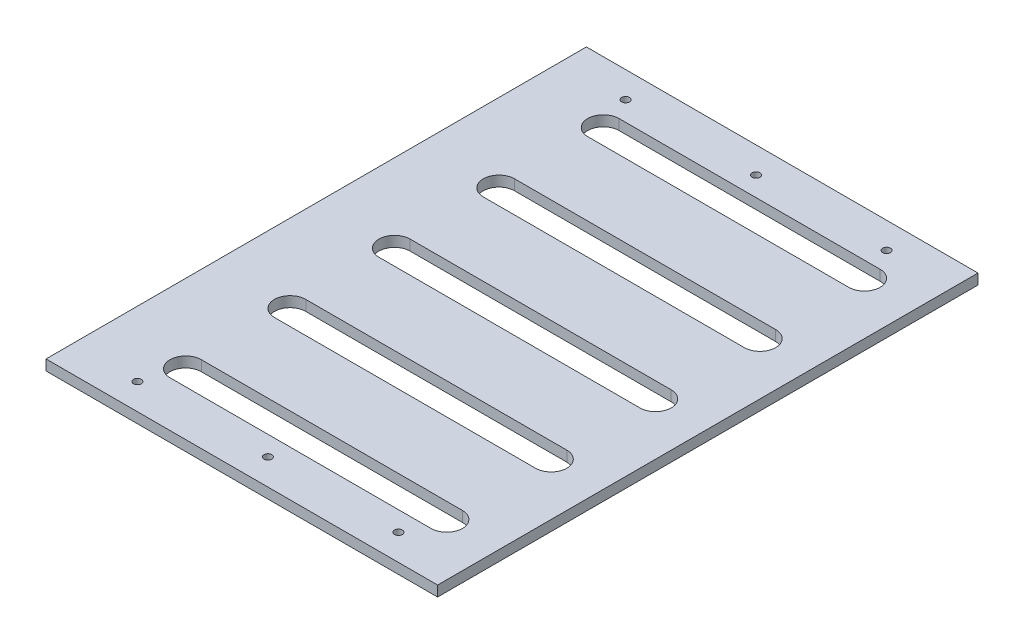
SolidWorks part; units mm, degrees
ref_plane "Front" through (0, 0, 0) normal (0, 0, 1) x (1, 0, 0)
ref_plane "Top" through (0, 0, 0) normal (0, 1, 0) x (1, 0, 0)
ref_plane "Right" through (0, 0, 0) normal (1, 0, 0) x (0, 0, -1)
sketch "草图1" plane through (0, 0, 0) normal (0, 1, 0) x (1, 0, 0)
  line L1 (0, 0) -> (150, 0)
  line L2 (0, 0) -> (0, 207)
  line L3 (0, 207) -> (150, 207)
  line L4 (150, 0) -> (150, 207)
  dimension "D1" = 150
  dimension "D2" = 207
extrude "凸台-拉伸1" add sketch "草图1" along normal blind 4
sketch "草图2" plane through (0, 4, 0) normal (0, 1, 0) x (1, 0, 0)
  line L0 (30, 183.5) -> (130, 183.5) construction
  line L1 (30, 189.5) -> (130, 189.5)
  line L2 (30, 177.5) -> (130, 177.5)
  line L4 (150, 103.5) -> (0, 103.5) construction
  line L5 (150, 0) -> (150, 207) construction
  line L6 (0, 207) -> (0, 0) construction
  line L7 (30, 143.5) -> (130, 143.5) construction
  line L8 (30, 149.5) -> (130, 149.5)
  line L9 (30, 137.5) -> (130, 137.5)
  line L13 (30, 103.5) -> (130, 103.5) construction
  line L14 (30, 97.5) -> (130, 97.5)
  line L15 (30, 109.5) -> (130, 109.5)
  line L16 (30, 63.5) -> (130, 63.5) construction
  line L17 (30, 57.5) -> (130, 57.5)
  line L18 (30, 69.5) -> (130, 69.5)
  line L19 (30, 23.5) -> (130, 23.5) construction
  line L20 (30, 17.5) -> (130, 17.5)
  line L21 (30, 29.5) -> (130, 29.5)
  line L24 (30, 103.5) -> (130, 103.5) construction
  line L25 (30, 109.5) -> (130, 109.5)
  line L26 (30, 97.5) -> (130, 97.5)
  line L27 (30, 103.5) -> (130, 103.5) construction
  line L28 (30, 109.5) -> (130, 109.5)
  line L29 (30, 97.5) -> (130, 97.5)
  arc A0 (30, 189.5) -> (30, 177.5) centre (30, 183.5) ccw
  arc A1 (130, 177.5) -> (130, 189.5) centre (130, 183.5) ccw
  arc A2 (30, 149.5) -> (30, 137.5) centre (30, 143.5) ccw
  arc A3 (130, 137.5) -> (130, 149.5) centre (130, 143.5) ccw
  arc A6 (30, 97.5) -> (30, 109.5) centre (30, 103.5) cw
  arc A7 (130, 109.5) -> (130, 97.5) centre (130, 103.5) cw
  arc A8 (30, 57.5) -> (30, 69.5) centre (30, 63.5) cw
  arc A9 (130, 69.5) -> (130, 57.5) centre (130, 63.5) cw
  arc A10 (30, 17.5) -> (30, 29.5) centre (30, 23.5) cw
  arc A11 (130, 29.5) -> (130, 17.5) centre (130, 23.5) cw
  arc A16 (30, 109.5) -> (30, 97.5) centre (30, 103.5) ccw
  arc A17 (130, 97.5) -> (130, 109.5) centre (130, 103.5) ccw
  point P2 (80, 183.5)
  point P16 (80, 143.5)
  point P29 (80, 103.5)
  point P36 (80, 63.5)
  point P43 (80, 23.5)
  point P50 (80, 103.5)
  point P57 (80, 103.5)
  point P64 (80, 103.5)
  dimension "D2" = 6
  dimension "D1" = 80
  dimension "D3" = 30
  dimension "D4" = 100
  dimension "D5" = 3
extrude "切除-拉伸1" cut sketch "草图2" against normal through all
sketch "草图3" plane through (0, 4, 0) normal (0, 1, 0) x (1, 0, 0)
  line L0 (0, 197) -> (150, 197) construction
  line L1 (0, 207) -> (0, 0) construction
  line L2 (150, 0) -> (150, 207) construction
  line L3 (150, 10) -> (0, 10) construction
  line L4 (150, 207) -> (0, 207) construction
  line L6 (0, 0) -> (150, 0) construction
  line L7 (0, 103.5) -> (150, 103.5) construction
  circle A0 centre (125, 197) radius 1.5
  circle A1 centre (75, 197) radius 1.5
  circle A2 centre (25, 197) radius 1.5
  circle A3 centre (25, 10) radius 1.5
  circle A4 centre (75, 10) radius 1.5
  circle A5 centre (125, 10) radius 1.5
  point P26 (130.7953, 247)
  dimension "D3" = 3
  dimension "D4" = 3
  dimension "D5" = 3
  dimension "D1" = 10
  dimension "D2" = 10
  dimension "D6" = 25
  dimension "D7" = 25
extrude "切除-拉伸2" cut sketch "草图3" against normal through all
